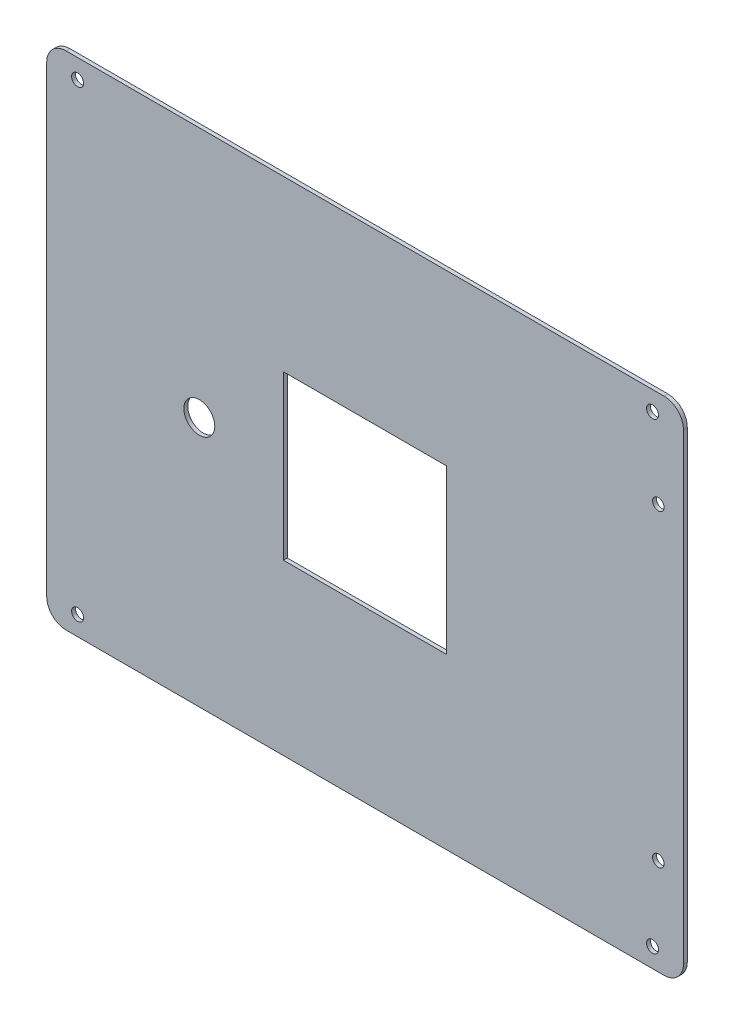
SolidWorks part; units mm, degrees
ref_plane "前视基准面" through (0, 0, 0) normal (0, 0, 1) x (1, 0, 0)
ref_plane "上视基准面" through (0, 0, 0) normal (0, 1, 0) x (1, 0, 0)
ref_plane "右视基准面" through (0, 0, 0) normal (1, 0, 0) x (0, 0, -1)
sketch "草图1" plane through (0, 0, 0) normal (0, 0, 1) x (1, 0, 0)
  line L1 (-77.5, 65) -> (77.5, 65)
  line L2 (-82.5, 60) -> (-82.5, -60)
  line L3 (-77.5, -65) -> (77.5, -65)
  line L4 (82.5, 60) -> (82.5, -60)
  line L5 (-82.5, 65) -> (82.5, -65) construction
  line L6 (-82.5, -65) -> (82.5, 65) construction
  circle A0 centre (-74.5, 60) radius 1.55
  circle A1 centre (74.5, 60) radius 1.55
  circle A2 centre (74.5, -60) radius 1.55
  circle A3 centre (-74.5, -60) radius 1.55
  arc A6 (77.5, 65) -> (82.5, 60) centre (77.5, 60) cw
  arc A7 (77.5, -65) -> (82.5, -60) centre (77.5, -60) ccw
  arc A8 (-82.5, -60) -> (-77.5, -65) centre (-77.5, -60) ccw
  arc A9 (-77.5, 65) -> (-82.5, 60) centre (-77.5, 60) ccw
  point P0 (0, 0)
  point P5 (0, 0)
  point P19 (43.0615, -40.5)
  dimension "D5" = 3.1
  dimension "D7" = 8
  dimension "D10" = 5
  dimension "D12" = 3.1
  dimension "D13" = 3.1
  dimension "D14" = 3.1
  dimension "D1" = 165
  dimension "D2" = 130
  dimension "D3" = 8
  dimension "D4" = 120
  dimension "D6" = 8
  dimension "D8" = 8
extrude "凸台-拉伸1" add sketch "草图1" along normal blind 1
sketch "草图2" plane through (0, 0, 1) normal (0, 0, 1) x (1, 0, 0)
sketch "草图3" plane through (0, 0, 1) normal (0, 0, 1) x (1, 0, 0)
  circle A1 centre (76, 40) radius 1.5
  circle A2 centre (76, -40) radius 1.5
  dimension "D1" = 12
extrude "切除-拉伸2" cut sketch "草图3" against normal blind 10
sketch "草图4" plane through (0, 0, 1) normal (0, 0, 1) x (1, 0, 0)
  circle A0 centre (-42.9512, 0) radius 4
extrude "切除-拉伸3" cut sketch "草图4" against normal blind 10
sketch "草图5" plane through (0, 0, 1) normal (0, 0, 1) x (1, 0, 0)
  line L1 (-21.15, 21.15) -> (21.15, 21.15)
  line L2 (-21.15, 21.15) -> (-21.15, -21.15)
  line L3 (-21.15, -21.15) -> (21.15, -21.15)
  line L4 (21.15, 21.15) -> (21.15, -21.15)
  line L5 (-21.15, 21.15) -> (21.15, -21.15) construction
  line L6 (-21.15, -21.15) -> (21.15, 21.15) construction
  point P0 (0, 0)
  dimension "D1" = 42.3
  dimension "D2" = 42.3
extrude "切除-拉伸4" cut sketch "草图5" against normal blind 10
